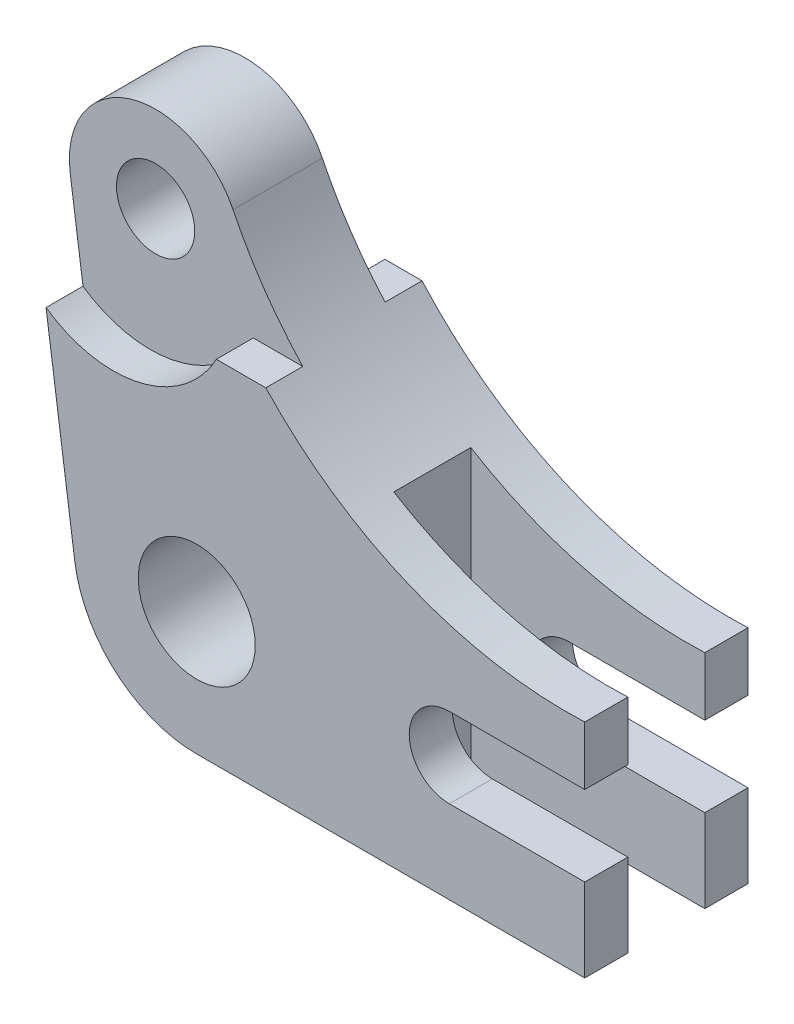
SolidWorks part; units mm, degrees
material "AISI 1020"
ref_plane "Front Plane" through (0, 0, 0) normal (0, 0, 1) x (1, 0, 0)
ref_plane "Top Plane" through (0, 0, 0) normal (0, 1, 0) x (1, 0, 0)
ref_plane "Right Plane" through (0, 0, 0) normal (1, 0, 0) x (0, 0, -1)
sketch "Sketch1" plane through (0, 0, 0) normal (0, 0, 1) x (1, 0, 0)
  line L0 (0, 0) -> (-12.6821, 47.3304) construction
  line L1 (0, 0) -> (0, 38.1205) construction
  line L2 (0, 0) -> (63, 0) construction
  line L3 (0, -20) -> (63, -20)
  line L4 (63, -20) -> (63, -6.5)
  line L5 (63, -6.5) -> (41, -6.5)
  line L6 (-26.547, 45.39) -> (-19.807, -2.7719)
  line L7 (63, 16) -> (63, 6.5)
  line L8 (63, 6.5) -> (41, 6.5)
  circle A0 centre (0, 0) radius 9.5
  circle A1 centre (-12.6821, 47.3304) radius 6.35
  arc A2 (-0.1073, 53.4844) -> (-26.547, 45.39) centre (-12.6821, 47.3304) ccw
  arc A3 (-19.807, -2.7719) -> (0, -20) centre (0, 0) ccw
  arc A4 (-0.1073, 53.4844) -> (63, 16) centre (60.0725, 82.936) ccw
  arc A5 (41, 6.5) -> (41, -6.5) centre (41, 0) ccw
  point P7 (1.3179, 47.3304)
  point P16 (0, 0)
  point P17 (-19.8596, -2.3655)
  point P18 (0, 0)
  point P21 (63, 26)
  point P23 (-26.6821, 47.3304)
  point P24 (1.3179, 47.3304)
  point P25 (0, 0)
  dimension "D1" = 19
  dimension "D4" = 12.7
  dimension "D5" = 14
  dimension "D6" = 20
  dimension "D9" = 67
  dimension "D11" = 13
  dimension "D2" = 15
  dimension "D3" = 49
  dimension "D7" = 63
  dimension "D8" = 22
  dimension "D10" = 36
extrude "Boss-Extrude1" add sketch "Sketch1" along normal blind 26.5
sketch "Sketch4" plane through (63, 0, 0) normal (1, 0, 0) x (0, 0, -1)
  line L0 (-26.5, -20) -> (0, -20) construction
  line L1 (-19.5, -20) -> (-7, -20)
  line L2 (-19.5, -20) -> (-19.5, 16)
  line L3 (-19.5, 16) -> (-7, 16)
  line L4 (-7, -20) -> (-7, 16)
  line L5 (-26.5, 16) -> (0, 16) construction
  line L6 (0, -20) -> (0, -6.5) construction
  line L7 (0, -6.5) -> (-26.5, -6.5) construction
  line L8 (-26.5, -6.5) -> (-26.5, -20) construction
  line L9 (0, 6.5) -> (0, 16) construction
  line L10 (0, 16) -> (-26.5, 16) construction
  line L11 (-26.5, 16) -> (-26.5, 6.5) construction
  line L12 (-26.5, 6.5) -> (0, 6.5) construction
  line L13 (0, -20) -> (0, -6.5)
  line L14 (0, -6.5) -> (-26.5, -6.5)
  line L15 (-26.5, -6.5) -> (-26.5, -20)
  line L16 (-26.5, -20) -> (0, -20)
  line L17 (0, 6.5) -> (0, 16)
  line L18 (0, 16) -> (-26.5, 16)
  line L19 (-26.5, 16) -> (-26.5, 6.5)
  line L20 (-26.5, 6.5) -> (0, 6.5)
  line M8 (0, 16) -> (-26.5, 16)
  line M10 (-26.5, 6.5) -> (0, 6.5)
  dimension "D1" = 7
  dimension "D2" = 7
extrude "Cut-Extrude2" cut sketch "Sketch4" against normal blind 38 contours L4 L2 M10 M8 | L14 L4 L2 M10 | L4 L14 L2 L1
sketch "Sketch8" plane through (0, 16, 0) normal (0, -1, 0) x (1, 0, 0)
  line L4 (57.145, 19.5) -> (25, 19.5)
  line L5 (25, 19.5) -> (25, 7)
  line L6 (25, 7) -> (57.145, 7)
  line L7 (57.145, 7) -> (57.145, 19.5)
  line L8 (57.145, 19.5) -> (25, 19.5)
  line L9 (25, 19.5) -> (25, 7)
  line L10 (25, 7) -> (57.145, 7)
  line L11 (57.145, 7) -> (57.145, 19.5)
  dimension "D1" = 0
extrude "Cut-Extrude3" cut sketch "Sketch8" against normal through all
sketch "Sketch9" plane through (0, 0, 26.5) normal (0, 0, 1) x (1, 0, 0)
  line L0 (-13.5501, 46.0945) -> (-13.5501, 37.0945) construction
  line L1 (-13.5501, 37.0945) -> (11.5247, 37.0945) construction
  line L2 (11.2099, 37.0945) -> (3.1831, 37.0945)
  line L8 (-26.547, 45.39) -> (-19.807, -2.7719)
  line L9 (0, -20) -> (63, -20)
  line L10 (63, -20) -> (63, -6.5)
  line L11 (63, -6.5) -> (41, -6.5)
  line L12 (41, 6.5) -> (63, 6.5)
  line L13 (63, 6.5) -> (63, 16)
  line L14 (-26.547, 45.39) -> (-19.807, -2.7719)
  line L15 (0, -20) -> (63, -20)
  line L16 (63, -20) -> (63, -6.5)
  line L17 (63, -6.5) -> (41, -6.5)
  line L18 (41, 6.5) -> (63, 6.5)
  line L19 (63, 6.5) -> (63, 16)
  arc A0 (3.1831, 37.0945) -> (-24.4696, 30.5457) centre (-13.5501, 46.0945) cw
  arc A4 (-0.1073, 53.4844) -> (-26.547, 45.39) centre (-12.6821, 47.3304) ccw
  arc A5 (-19.807, -2.7719) -> (0, -20) centre (0, 0) ccw
  arc A6 (41, 6.5) -> (41, -6.5) centre (41, 0) ccw
  arc A7 (-0.1073, 53.4844) -> (63, 16) centre (60.0725, 82.936) ccw
  arc A8 (-0.1073, 53.4844) -> (-26.547, 45.39) centre (-12.6821, 47.3304) ccw
  arc A9 (-19.807, -2.7719) -> (0, -20) centre (0, 0) ccw
  arc A10 (41, 6.5) -> (41, -6.5) centre (41, 0) ccw
  arc A11 (-0.1073, 53.4844) -> (63, 16) centre (60.0725, 82.936) ccw
  arc M13 (-0.1073, 53.4844) -> (-26.547, 45.39) centre (-12.6821, 47.3304) ccw
  line M14 (-26.547, 45.39) -> (-19.807, -2.7719)
  arc M22 (63, 16) -> (-0.1073, 53.4844) centre (60.0725, 82.936) cw
  circle M23 centre (-12.6821, 47.3304) radius 6.35
  dimension "D3" = 19
  dimension "D1" = 9
  dimension "D2" = 0
extrude "Cut-Extrude4" cut sketch "Sketch9" against normal blind 6 contours A0 L2 M22 M13 M14 M23
sketch "Sketch10" plane through (0, 0, 0) normal (0, 0, -1) x (-1, 0, 0)
  line L0 (12.6821, 47.3304) -> (12.6821, 38.3304) construction
  line L1 (12.6821, 38.3304) -> (-13.2327, 38.3304) construction
  line L2 (-10.0791, 38.3304) -> (-4.0511, 38.3304)
  line L6 (-63, 16) -> (-63, 6.5)
  line L7 (-63, 6.5) -> (-41, 6.5)
  line L8 (-41, -6.5) -> (-63, -6.5)
  line L9 (-63, -6.5) -> (-63, -20)
  line L10 (-63, -20) -> (0, -20)
  line L11 (19.807, -2.7719) -> (26.547, 45.39)
  line L12 (-63, 16) -> (-63, 6.5)
  line L13 (-63, 6.5) -> (-41, 6.5)
  line L14 (-41, -6.5) -> (-63, -6.5)
  line L15 (-63, -6.5) -> (-63, -20)
  line L16 (-63, -20) -> (0, -20)
  line L17 (19.807, -2.7719) -> (26.547, 45.39)
  arc A0 (-4.0511, 38.3304) -> (24.7667, 32.6688) centre (12.6821, 47.3304) ccw
  arc A4 (26.547, 45.39) -> (0.1073, 53.4844) centre (12.6821, 47.3304) ccw
  arc A5 (-63, 16) -> (0.1073, 53.4844) centre (-60.0725, 82.936) ccw
  arc A6 (-41, -6.5) -> (-41, 6.5) centre (-41, 0) ccw
  arc A7 (0, -20) -> (19.807, -2.7719) centre (0, 0) ccw
  arc A8 (26.547, 45.39) -> (0.1073, 53.4844) centre (12.6821, 47.3304) ccw
  arc A9 (-63, 16) -> (0.1073, 53.4844) centre (-60.0725, 82.936) ccw
  arc A10 (-41, -6.5) -> (-41, 6.5) centre (-41, 0) ccw
  arc A11 (0, -20) -> (19.807, -2.7719) centre (0, 0) ccw
  arc M12 (26.547, 45.39) -> (0.1073, 53.4844) centre (12.6821, 47.3304) ccw
  arc M13 (0.1073, 53.4844) -> (-63, 16) centre (-60.0725, 82.936) cw
  circle M23 centre (12.6821, 47.3304) radius 6.35
  dimension "D3" = 19
  dimension "D2" = 9
  dimension "D1" = 0
extrude "Cut-Extrude5" cut sketch "Sketch10" against normal blind 6 contours L2 A0 L17 M12 M13 M23
equation "\"a\"= 63"
equation "\"b\"= 20"
equation "\"c\"= 26.50"
